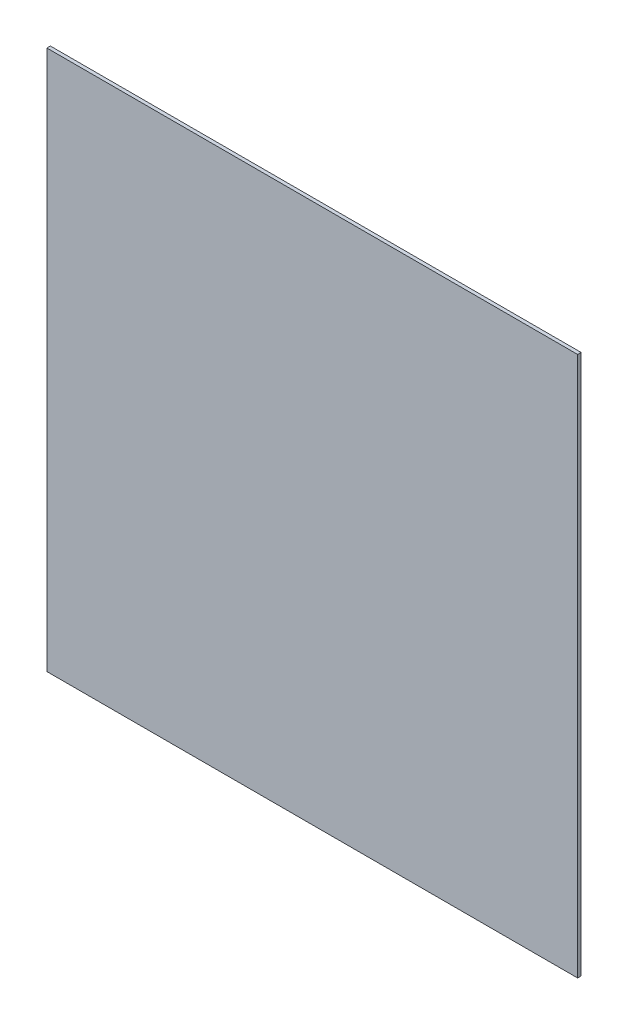
SolidWorks part; units mm, degrees
ref_plane "Płaszczyzna przednia" through (0, 0, 0) normal (0, 0, 1) x (1, 0, 0)
ref_plane "Płaszczyzna górna" through (0, 0, 0) normal (0, 1, 0) x (1, 0, 0)
ref_plane "Płaszczyzna prawa" through (0, 0, 0) normal (1, 0, 0) x (0, 0, -1)
sketch "Szkic1" plane through (0, 0, 0) normal (0, 0, 1) x (1, 0, 0)
  line L1 (0, 0) -> (456, 0)
  line L2 (0, 0) -> (0, 464)
  line L3 (0, 464) -> (456, 464)
  line L4 (456, 0) -> (456, 464)
  dimension "D1" = 464
  dimension "D2" = 456
extrude "Dodanie-wyciągnięcie1" add sketch "Szkic1" along normal blind 3
